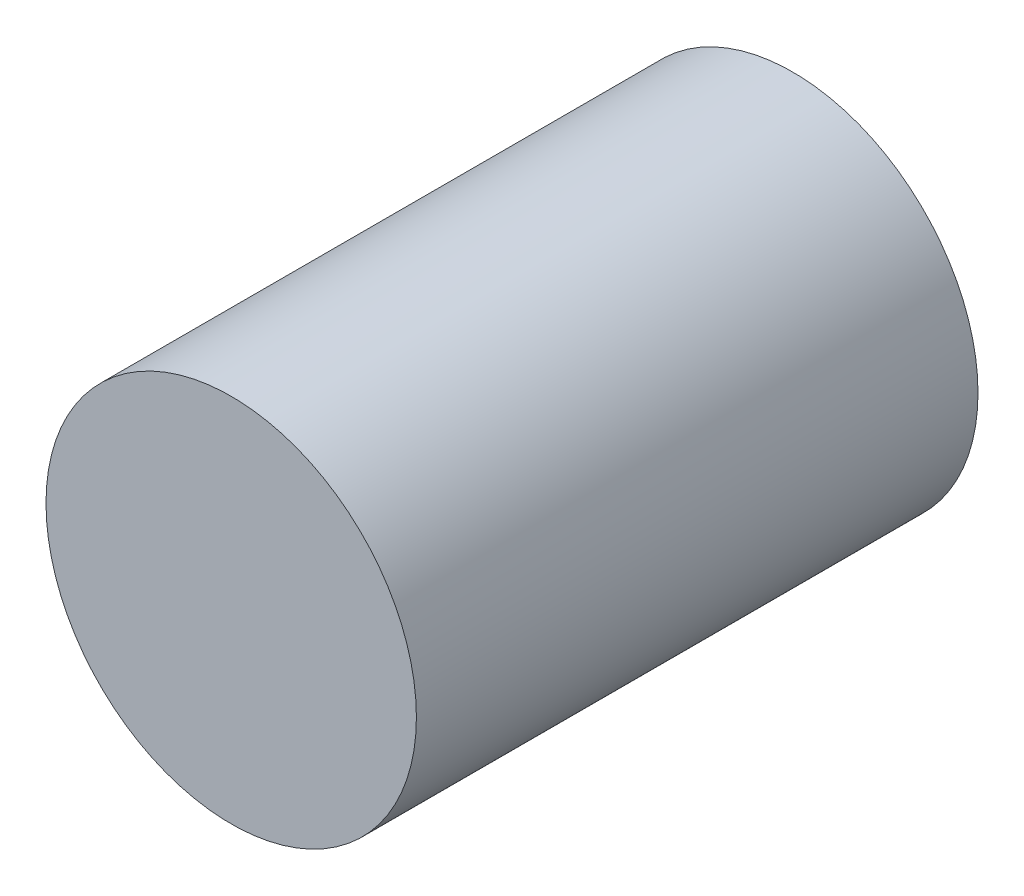
SolidWorks part; units mm, degrees
material "AISI 1015 Steel, Cold Drawn (SS)"
ref_plane "Front Plane" through (0, 0, 0) normal (0, 0, 1) x (1, 0, 0)
ref_plane "Top Plane" through (0, 0, 0) normal (0, 1, 0) x (1, 0, 0)
ref_plane "Right Plane" through (0, 0, 0) normal (1, 0, 0) x (0, 0, -1)
sketch "Sketch1" plane through (0, 0, 0) normal (0, 0, 1) x (1, 0, 0)
  circle A0 centre (0, 0) radius 3.1
  dimension "D1" = 6.2
extrude "Boss-Extrude1" add sketch "Sketch1" along normal blind 9.4
